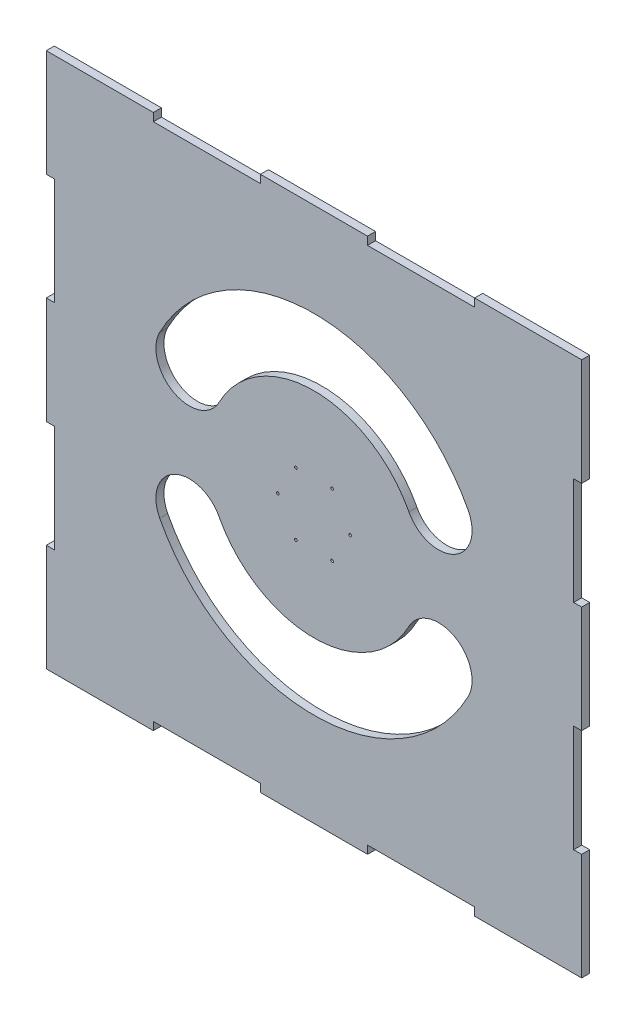
SolidWorks part; units mm, degrees
ref_plane "Alzado" through (0, 0, 0) normal (0, 0, 1) x (1, 0, 0)
ref_plane "Planta" through (0, 0, 0) normal (0, 1, 0) x (1, 0, 0)
ref_plane "Vista lateral" through (0, 0, 0) normal (1, 0, 0) x (0, 0, -1)
sketch "Sketch1" plane through (0, 0, 0) normal (0, 0, 1) x (1, 0, 0)
  line L0 (-100, 100) -> (-60, 100)
  line L1 (-100, 100) -> (-60, 100)
  line L2 (-100, 100) -> (-100, 60)
  line L3 (-100, -100) -> (-60, -100)
  line L4 (100, 100) -> (100, 60)
  line L7 (-60, 100) -> (-60, 97)
  line L8 (-60, 97) -> (-20, 97)
  line L9 (-20, 97) -> (-20, 100)
  line L10 (-20, 100) -> (20, 100)
  line L11 (20, 100) -> (20, 97)
  line L12 (20, 97) -> (60, 97)
  line L13 (60, 97) -> (60, 100)
  line L15 (60, -97) -> (60, -100)
  line L16 (20, -97) -> (60, -97)
  line L17 (20, -100) -> (20, -97)
  line L18 (-20, -97) -> (-20, -100)
  line L19 (-60, -97) -> (-20, -97)
  line L20 (-60, -100) -> (-60, -97)
  line L21 (-20, 100) -> (20, 100)
  line L22 (60, 100) -> (100, 100)
  line L23 (-20, -100) -> (20, -100)
  line L24 (60, -100) -> (100, -100)
  line L25 (100, 60) -> (97, 60)
  line L26 (97, 60) -> (97, 20)
  line L27 (97, 20) -> (100, 20)
  line L28 (100, 20) -> (100, -20)
  line L29 (100, -20) -> (97, -20)
  line L30 (97, -20) -> (97, -60)
  line L31 (97, -60) -> (100, -60)
  line L33 (-97, -60) -> (-100, -60)
  line L34 (-97, -20) -> (-97, -60)
  line L35 (-100, -20) -> (-97, -20)
  line L36 (-97, 20) -> (-100, 20)
  line L37 (-100, 60) -> (-97, 60)
  line L38 (-97, 60) -> (-97, 20)
  line L39 (-100, 20) -> (-100, -20)
  line L40 (-100, -60) -> (-100, -100)
  line L41 (100, 20) -> (100, -20)
  line L42 (100, -60) -> (100, -100)
  line L49 (50.9902, 12.5) -> (49.5238, 12.1405) construction
  line L50 (49.5238, 12.1405) -> (50.9902, 12.5) construction
  line L54 (0, 0) -> (-32.6587, 0) construction
  line L56 (49.5238, 12.1405) -> (50.9902, 12.5) construction
  arc A0 (35.4649, 18.4998) -> (-35.4649, 18.4998) centre (0, 0) ccw
  arc A1 (57.6304, 30.0622) -> (-57.6304, 30.0622) centre (0, 0) ccw
  arc A6 (35.4649, 18.4998) -> (57.6304, 30.0622) centre (46.5476, 24.281) ccw
  arc A7 (35.4649, -18.4998) -> (57.6304, -30.0622) centre (46.5476, -24.281) cw
  arc A8 (-35.4649, -18.4998) -> (-57.6304, -30.0622) centre (-46.5476, -24.281) ccw
  arc A9 (-35.4649, 18.4998) -> (-57.6304, 30.0622) centre (-46.5476, 24.281) cw
  arc A10 (-35.4649, -18.4998) -> (35.4649, -18.4998) centre (0, 0) ccw
  arc A11 (-57.6304, -30.0622) -> (57.6304, -30.0622) centre (0, 0) ccw
  point P0 (0, 0)
  point P54 (0, 0)
  point P55 (0, 0)
  point P57 (0, 0)
  dimension "D15" = 80
  dimension "D16" = 130
  dimension "D1" = 200
  dimension "D2" = 200
  dimension "D3" = 40
  dimension "D4" = 40
  dimension "D5" = 40
  dimension "D6" = 40
  dimension "D7" = 3
  dimension "D8" = 3
  dimension "D9" = 3
  dimension "D10" = 40
  dimension "D11" = 40
  dimension "D12" = 40
  dimension "D13" = 40
  dimension "D14" = 3
extrude "Boss-Extrude1" add sketch "Sketch1" along normal blind 3 contours L42 L31 L30 L29 L28 L27 L26 L25 L4 L22 L13 L12 L11 L10 L9 L8 L7 L0 L2 L37 L38 L36 L39 L35 L34 L33 L40 L3 L20 L19 L18 L23 L17 L16 L15 L24 A11 A8 A10 A7 A0 A9 A1 A6
sketch "Sketch2" plane through (0, 0, 3) normal (0, 0, 1) x (1, 0, 0)
  line L1 (0, 0) -> (-14, 0) construction
  line L2 (-14, 0) -> (-13.5, 0) construction
  circle A0 centre (-13.5, 0) radius 0.5
  circle A1 centre (-6.75, 11.6913) radius 0.5
  circle A2 centre (6.75, 11.6913) radius 0.5
  circle A3 centre (13.5, 0) radius 0.5
  circle A4 centre (6.75, -11.6913) radius 0.5
  circle A5 centre (-6.75, -11.6913) radius 0.5
  point P20 (0, 0)
  dimension "D1" = 6
  dimension "D2" = 14
  dimension "D3" = 0.5
extrude "Cut-Extrude1" cut sketch "Sketch2" against normal blind 3
